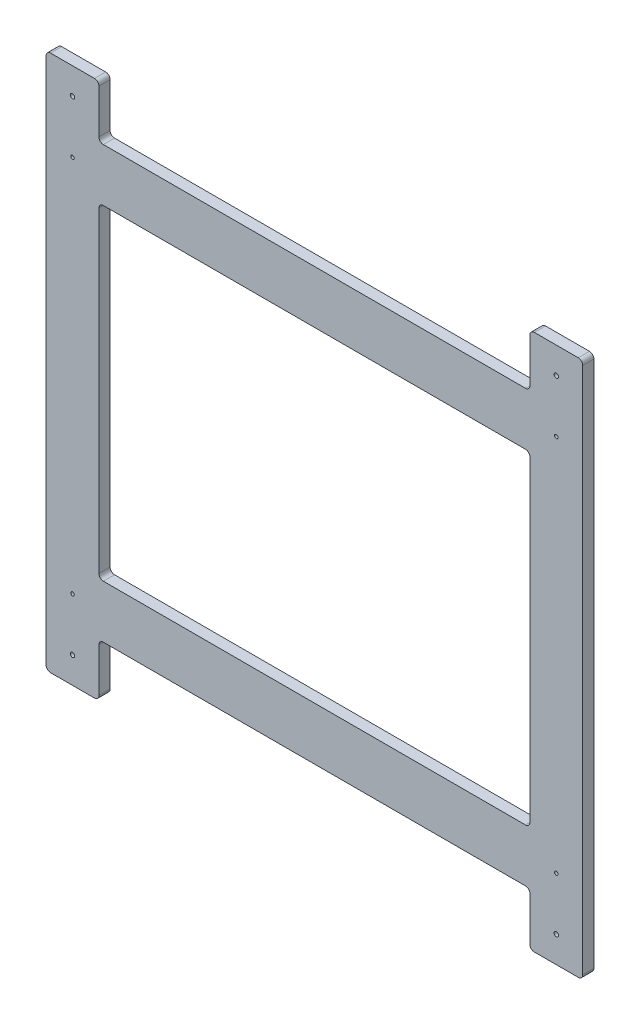
SolidWorks part; units mm, degrees
ref_plane "Front Plane" through (0, 0, 0) normal (0, 0, 1) x (1, 0, 0)
ref_plane "Top Plane" through (0, 0, 0) normal (0, 1, 0) x (1, 0, 0)
ref_plane "Right Plane" through (0, 0, 0) normal (1, 0, 0) x (0, 0, -1)
sketch "Sketch7" plane through (0, 0, 0) normal (0, 0, 1) x (1, 0, 0)
  line L1 (-119.9, -92.4) -> (119.9, -92.4)
  line L2 (-122.4, -89.9) -> (-122.4, 89.9)
  line L3 (-119.9, 92.4) -> (119.9, 92.4)
  line L4 (122.4, -89.9) -> (122.4, 89.9)
  line L5 (-122.4, -92.4) -> (122.4, 92.4) construction
  line L6 (-122.4, 92.4) -> (122.4, -92.4) construction
  line L7 (-119.9, -122.4) -> (119.9, -122.4)
  line L8 (-152.4, -120.7432) -> (-152.4, 102.187)
  line L9 (-119.9, 122.4) -> (119.9, 122.4)
  line L10 (152.4, -102.187) -> (152.4, 120.7432)
  line L11 (-152.4, -120.7432) -> (152.4, 120.7432) construction
  line L12 (-152.4, 102.187) -> (152.4, -102.187) construction
  line L14 (-152.4, 102.187) -> (-152.4, 149.9)
  line L15 (-149.9, 152.4) -> (-124.9, 152.4)
  line L16 (-122.4, 124.9) -> (-122.4, 149.9)
  line L18 (122.4, 124.9) -> (122.4, 149.9)
  line L19 (124.9, 152.4) -> (149.9, 152.4)
  line L20 (152.4, 120.7432) -> (152.4, 149.9)
  line L22 (-152.4, -120.7432) -> (-152.4, -149.9)
  line L23 (-149.9, -152.4) -> (-124.9, -152.4)
  line L24 (-122.4, -124.9) -> (-122.4, -149.9)
  line L26 (152.4, -102.187) -> (152.4, -149.9)
  line L27 (149.9, -152.4) -> (124.9, -152.4)
  line L28 (122.4, -124.9) -> (122.4, -149.9)
  arc A0 (119.9, 92.4) -> (122.4, 89.9) centre (119.9, 89.9) cw
  arc A1 (119.9, -92.4) -> (122.4, -89.9) centre (119.9, -89.9) ccw
  arc A2 (-119.9, -92.4) -> (-122.4, -89.9) centre (-119.9, -89.9) cw
  arc A3 (-122.4, 89.9) -> (-119.9, 92.4) centre (-119.9, 89.9) cw
  arc A4 (-152.4, -149.9) -> (-149.9, -152.4) centre (-149.9, -149.9) ccw
  arc A5 (-124.9, -152.4) -> (-122.4, -149.9) centre (-124.9, -149.9) ccw
  arc A6 (-119.9, -122.4) -> (-122.4, -124.9) centre (-119.9, -124.9) ccw
  arc A7 (119.9, -122.4) -> (122.4, -124.9) centre (119.9, -124.9) cw
  arc A8 (124.9, -152.4) -> (122.4, -149.9) centre (124.9, -149.9) cw
  arc A9 (152.4, -149.9) -> (149.9, -152.4) centre (149.9, -149.9) cw
  arc A10 (149.9, 152.4) -> (152.4, 149.9) centre (149.9, 149.9) cw
  arc A11 (122.4, 149.9) -> (124.9, 152.4) centre (124.9, 149.9) cw
  arc A12 (119.9, 122.4) -> (122.4, 124.9) centre (119.9, 124.9) ccw
  arc A13 (-119.9, 122.4) -> (-122.4, 124.9) centre (-119.9, 124.9) cw
  arc A14 (-124.9, 152.4) -> (-122.4, 149.9) centre (-124.9, 149.9) cw
  arc A15 (-152.4, 149.9) -> (-149.9, 152.4) centre (-149.9, 149.9) cw
  point P0 (0, 0)
  point P6 (0, 0)
  point P37 (-152.4, -152.4)
  point P40 (-122.4, -152.4)
  point P43 (-122.4, -122.4)
  point P46 (122.4, -122.4)
  point P49 (122.4, -152.4)
  point P56 (122.4, 152.4)
  point P59 (122.4, 122.4)
  point P62 (-122.4, 122.4)
  point P65 (-122.4, 152.4)
  dimension "D15" = 2.5
  dimension "D1" = 304.8
  dimension "D2" = 304.8
  dimension "D3" = 30
  dimension "D4" = 30
  dimension "D5" = 30
  dimension "D6" = 30
  dimension "D7" = 30
  dimension "D8" = 30
  dimension "D9" = 30
  dimension "D10" = 30
  dimension "D11" = 30
  dimension "D12" = 30
  dimension "D13" = 30
  dimension "D14" = 30
extrude "Boss-Extrude1" add sketch "Sketch7" along normal blind 6.35
hole_wizard "M3 Clearance Hole3" positions "Sketch8" profile "Sketch9" hole size "M3" standard "ANSI Metric" end condition up to next
sketch "Sketch8" plane through (0, 0, 6.35) normal (0, 0, 1) x (1, 0, 0)
  line L0 (152.4, -149.9) -> (152.4, 149.9) construction
  line L1 (-152.4, 149.9) -> (-152.4, -149.9) construction
  line L2 (-119.9, -122.4) -> (119.9, -122.4) construction
  line L3 (119.9, 92.4) -> (-119.9, 92.4) construction
  point P0 (-137.4, 107.4)
  point P2 (-137.4, -107.4)
  point P4 (137.4, -107.4)
  point P6 (137.4, 107.4)
  dimension "D1" = 15
  dimension "D2" = 15
  dimension "D3" = 15
  dimension "D4" = 15
sketch "Sketch9" plane through (-137.4, 107.4, 6.35) normal (1, 0, 0) x (0, -1, 0)
  line L0 (0, 0) -> (0, 6.35)
  line L1 (0, 6.35) -> (1, 6.35)
  line L2 (1, 6.35) -> (1, 0)
  line L5 (1, 0) -> (0, 0)
  line L11 (0, -6.35) -> (0, 107.95) construction
  dimension "Thru Hole Dia." = 2
  dimension "Thru Hole Depth" = 6.35
hole_wizard "M3 Clearance Hole2" positions "Sketch10" profile "Sketch11" hole size "M3" standard "ANSI Metric" end condition up to next
sketch "Sketch10" plane through (0, 0, 6.35) normal (0, 0, 1) x (1, 0, 0)
  line L0 (152.4, -149.9) -> (152.4, 149.9) construction
  line L1 (149.9, 152.4) -> (124.9, 152.4) construction
  line L2 (-152.4, 149.9) -> (-152.4, -149.9) construction
  line L3 (-149.9, -152.4) -> (-124.9, -152.4) construction
  point P0 (-137.4, 137.4)
  point P2 (137.4, 137.4)
  point P4 (137.4, -137.4)
  point P6 (-137.4, -137.4)
  dimension "D1" = 15
  dimension "D2" = 15
  dimension "D3" = 15
  dimension "D4" = 15
sketch "Sketch11" plane through (-137.4, 137.4, 6.35) normal (1, 0, 0) x (0, -1, 0)
  line L0 (0, 0) -> (0, 6.35)
  line L1 (0, 6.35) -> (1.25, 6.35)
  line L2 (1.25, 6.35) -> (1.25, 0)
  line L5 (1.25, 0) -> (0, 0)
  line L11 (0, -6.35) -> (0, 107.95) construction
  dimension "Thru Hole Dia." = 2.5
  dimension "Thru Hole Depth" = 6.35
